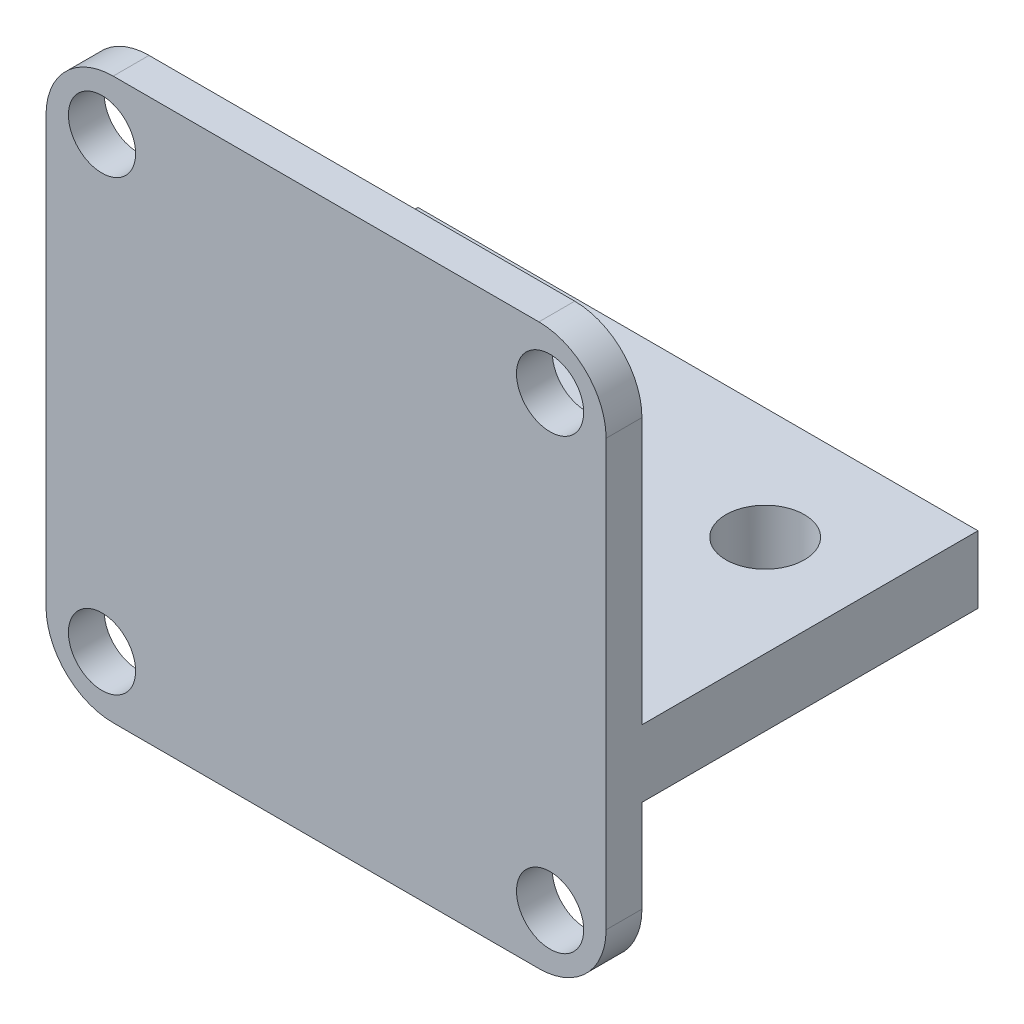
SolidWorks part; units mm, degrees
ref_plane "Front Plane" through (0, 0, 0) normal (0, 0, 1) x (1, 0, 0)
ref_plane "Top Plane" through (0, 0, 0) normal (0, 1, 0) x (1, 0, 0)
ref_plane "Right Plane" through (0, 0, 0) normal (1, 0, 0) x (0, 0, -1)
sketch "Sketch1" plane through (0, 0, 0) normal (0, 0, 1) x (1, 0, 0)
  line L1 (-9.5, -12.5) -> (9.5, -12.5)
  line L2 (-12.5, -9.5) -> (-12.5, 9.5)
  line L3 (-9.5, 12.5) -> (9.5, 12.5)
  line L4 (12.5, -9.5) -> (12.5, 9.5)
  line L5 (-12.5, -12.5) -> (12.5, 12.5) construction
  line L6 (-12.5, 12.5) -> (12.5, -12.5) construction
  line L7 (0, 12.5) -> (0, 0) construction
  line L8 (0, 0) -> (-12.5, 0) construction
  arc A0 (-9.5, -12.5) -> (-12.5, -9.5) centre (-9.5, -9.5) cw
  arc A1 (9.5, -12.5) -> (12.5, -9.5) centre (9.5, -9.5) ccw
  arc A2 (9.5, 12.5) -> (12.5, 9.5) centre (9.5, 9.5) cw
  arc A3 (-12.5, 9.5) -> (-9.5, 12.5) centre (-9.5, 9.5) cw
  circle A4 centre (-10, 10) radius 1.5
  circle A5 centre (10, 10) radius 1.5
  circle A6 centre (10, -10) radius 1.5
  circle A7 centre (-10, -10) radius 1.5
  point P0 (0, 0)
  dimension "D3" = 3
  dimension "D4" = 3
  dimension "D1" = 25
  dimension "D2" = 25
  dimension "D5" = 10
extrude "Boss-Extrude1" add sketch "Sketch1" along normal blind 1.6
sketch "Sketch2" plane through (0, 0, 0) normal (0, 0, -1) x (-1, 0, 0)
  line L0 (-12.5, 0) -> (12.5, 0) construction
  line L1 (-12.5, -9.5) -> (-12.5, 9.5) construction
  line L2 (12.5, 9.5) -> (12.5, -9.5) construction
  line L4 (-12.5, -5.375) -> (12.5, -5.375)
  line L5 (-12.5, -5.375) -> (-12.5, -2.375)
  line L6 (-12.5, -2.375) -> (12.5, -2.375)
  line L7 (12.5, -5.375) -> (12.5, -2.375)
  dimension "D1" = 2.375
  dimension "D2" = 3
extrude "Boss-Extrude2" add sketch "Sketch2" along normal blind 15
ref_plane "Plane1" through (0, 0, 0) normal (1, 0, 0) x (0, 0, -1)
sketch "Sketch3" plane through (0, -2.375, 0) normal (0, 1, 0) x (1, 0, 0)
  line L0 (0, 0) -> (0, 15.0798) construction
  line L1 (9.5, 0) -> (-9.5, 0) construction
  line L2 (0, -9.13) -> (0, 9.13) construction
  line L3 (-12.5, 0) -> (12.5, 0) construction
  circle A0 centre (-8, 10) radius 1.75
  circle A1 centre (8, 10) radius 1.75
  point P8 (0, 0)
  point P10 (-6.7891, 6.4585)
  dimension "D1" = 3.5
  dimension "D2" = 8
  dimension "D3" = 10
extrude "Cut-Extrude1" cut sketch "Sketch3" against normal through all
